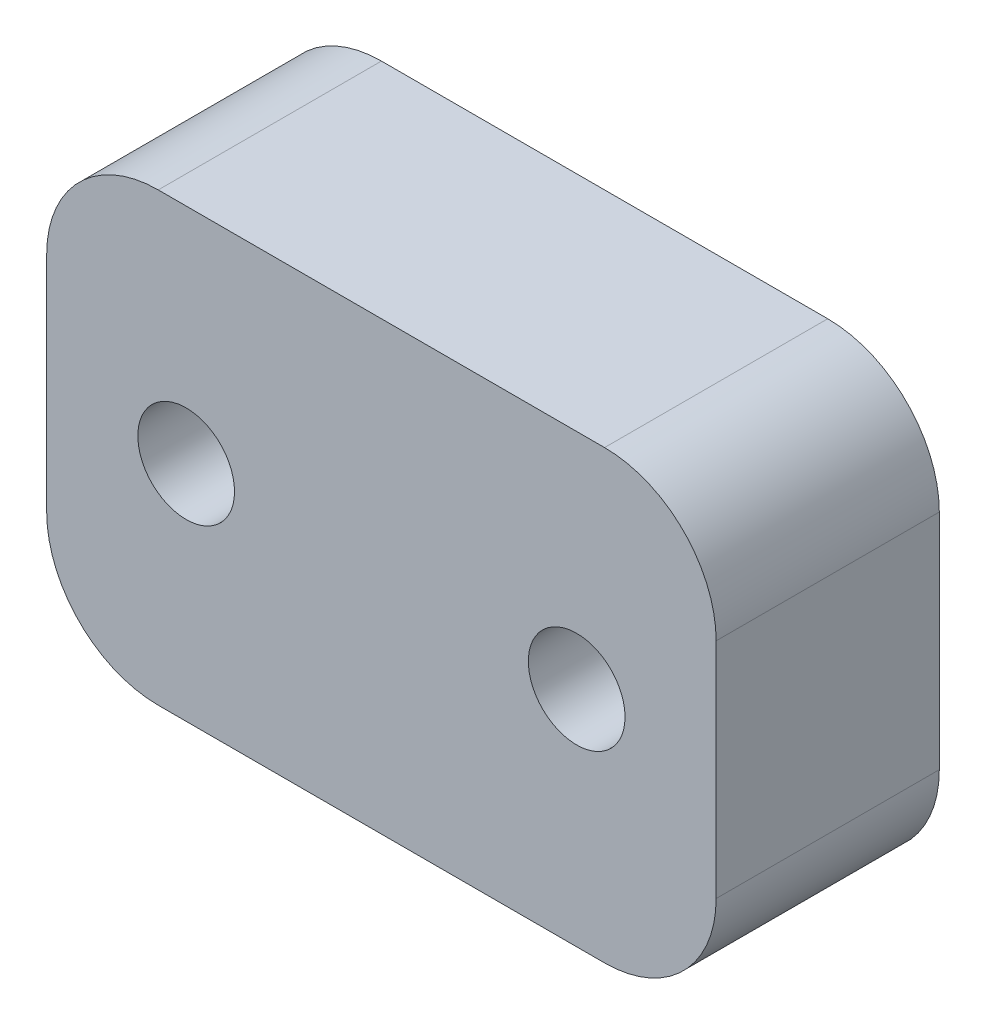
SolidWorks part; units mm, degrees
ref_plane "Alzado" through (0, 0, 0) normal (0, 0, 1) x (1, 0, 0)
ref_plane "Planta" through (0, 0, 0) normal (0, 1, 0) x (1, 0, 0)
ref_plane "Vista lateral" through (0, 0, 0) normal (1, 0, 0) x (0, 0, -1)
sketch "Croquis2" plane through (0, 0, 0) normal (0, 0, 1) x (1, 0, 0)
  line L0 (5.25, 0) -> (-5.25, 0) construction
  line L1 (9, -6) -> (-9, -6)
  line L2 (9, -6) -> (9, 6)
  line L3 (9, 6) -> (-9, 6)
  line L4 (-9, -6) -> (-9, 6)
  line L5 (9, -6) -> (-9, 6) construction
  line L6 (9, 6) -> (-9, -6) construction
  circle A0 centre (-5.25, 0) radius 1.3
  circle A1 centre (5.25, 0) radius 1.3
  point P0 (0, 0)
  point P9 (0, 0)
  point P12 (-5.25, -0.2054)
  dimension "D2" = 2.6
  dimension "D1" = 10.5
  dimension "D3" = 18
  dimension "D4" = 12
extrude "Saliente-Extruir1" add sketch "Croquis2" along normal blind 6
fillet "Redondeo1" radius 3 4 edges at (-9, -6, 3) (9, -6, 3) (-9, 6, 3) (9, 6, 3)
